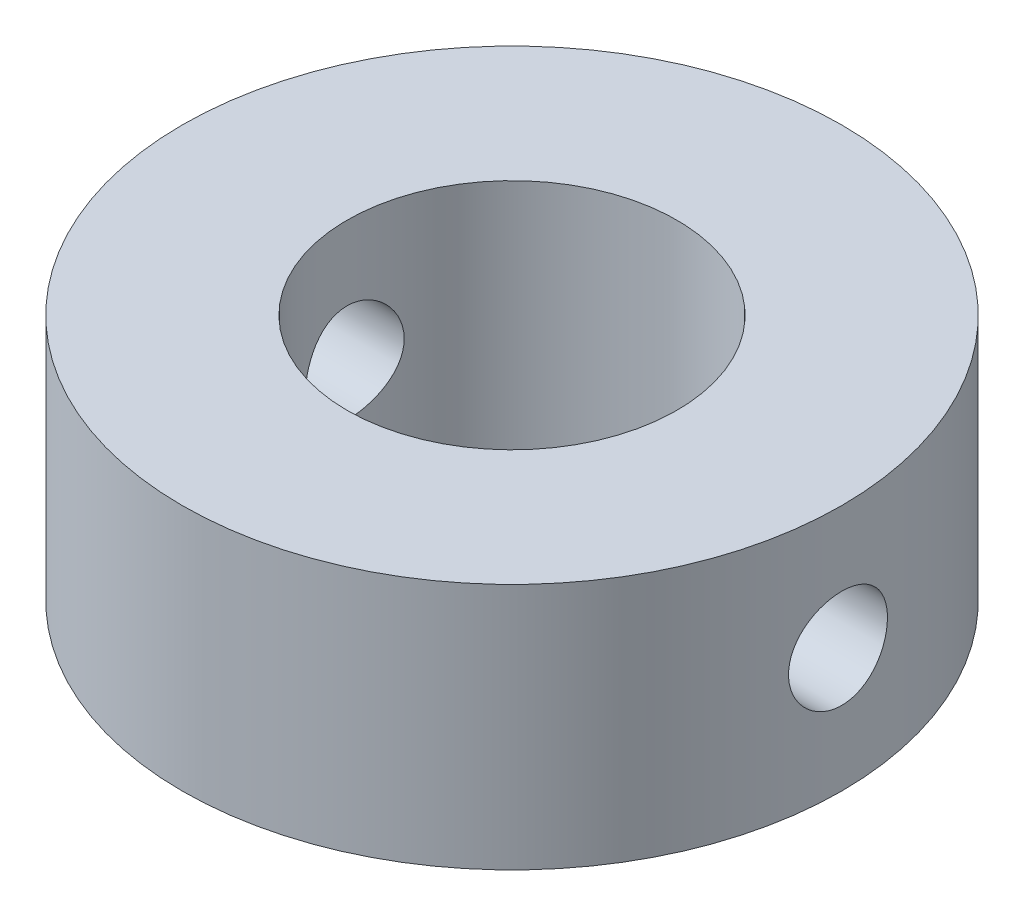
SolidWorks part; units mm, degrees
ref_plane "Front Plane" through (0, 0, 0) normal (0, 0, 1) x (1, 0, 0)
ref_plane "Top Plane" through (0, 0, 0) normal (0, 1, 0) x (1, 0, 0)
ref_plane "Right Plane" through (0, 0, 0) normal (1, 0, 0) x (0, 0, -1)
sketch "Sketch1" plane through (0, 0, 0) normal (0, 1, 0) x (1, 0, 0)
  circle A0 centre (0, 0) radius 5
  circle A1 centre (0, 0) radius 10
extrude "Boss-Extrude1" add sketch "Sketch1" along normal blind 7.5
sketch "Sketch2" plane through (0, 0, 0) normal (1, 0, 0) x (0, 0, -1)
  circle A0 centre (0, 3.75) radius 1.5
extrude "Cut-Extrude1" cut sketch "Sketch2" along normal blind 20.5 and the other way blind 19
